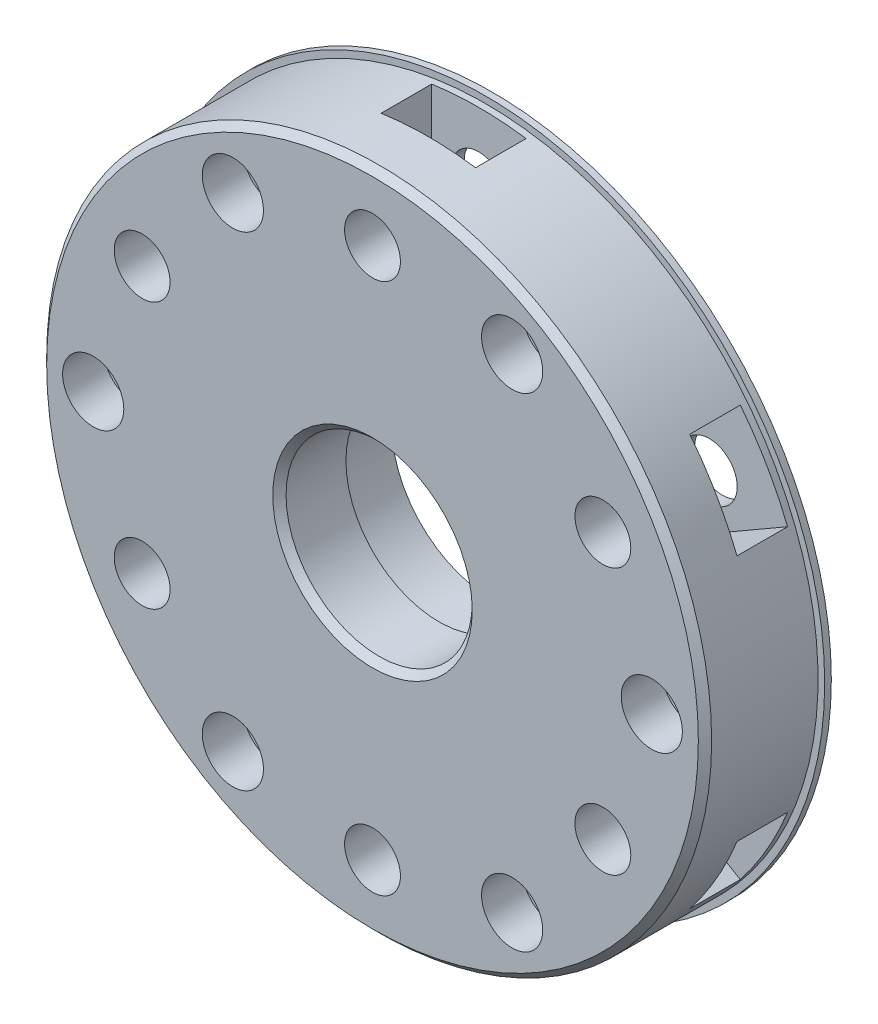
SolidWorks part; units mm, degrees
material "ABS"
ref_plane "Front Plane" through (0, 0, 0) normal (0, 0, 1) x (1, 0, 0)
ref_plane "Top Plane" through (0, 0, 0) normal (0, 1, 0) x (1, 0, 0)
ref_plane "Right Plane" through (0, 0, 0) normal (1, 0, 0) x (0, 0, -1)
sketch "Output Master Sketch" plane through (0, 0, 0) normal (0, 0, 1) x (1, 0, 0)
  circle A0 centre (0, 0) radius 21 construction
  circle A1 centre (21, 0) radius 3.05 construction
  circle A2 centre (10.5, -18.1865) radius 3.05 construction
  circle A3 centre (-10.5, -18.1865) radius 3.05 construction
  circle A4 centre (-21, 0) radius 3.05 construction
  circle A5 centre (-10.5, 18.1865) radius 3.05 construction
  circle A6 centre (10.5, 18.1865) radius 3.05 construction
  circle A7 centre (0, 0) radius 25
  point P17 (0, 0)
extrude "Boss-Extrude1" add sketch "Output Master Sketch" along normal blind 9
sketch "Sketch4" plane through (0, 0, 0) normal (0, 0, 1) x (1, 0, 0)
  circle A0 centre (21, 0) radius 3.05
  circle A1 centre (21, 0) radius 3.05 construction
  circle A2 centre (10.5, -18.1865) radius 3.05
  circle A3 centre (-10.5, -18.1865) radius 3.05
  circle A4 centre (-21, 0) radius 3.05
  circle A5 centre (-10.5, 18.1865) radius 3.05
  circle A6 centre (10.5, 18.1865) radius 3.05
  point P17 (0, 0)
  dimension "D1" = 6
extrude "Cut-Extrude1" cut sketch "Sketch4" along normal blind 4
sketch "Sketch5" plane through (0, 0, 0) normal (0, 0, -1) x (-1, 0, 0)
  circle A0 centre (0, 0) radius 25
  circle A1 centre (0, 0) radius 25.5
  circle A2 centre (0, 0) radius 25 construction
  dimension "D1" = 0.5
extrude "Boss-Extrude2" add sketch "Sketch5" against normal blind 0.5
sketch "Sketch6" plane through (0, 0, 0) normal (0, 0, -1) x (-1, 0, 0)
  circle A0 centre (-21, 0) radius 1.55
  circle A1 centre (-10.5, 18.1865) radius 1.55
  circle A2 centre (10.5, 18.1865) radius 1.55
  circle A3 centre (21, 0) radius 1.55
  circle A4 centre (10.5, -18.1865) radius 1.55
  circle A5 centre (-10.5, -18.1865) radius 1.55
  point P15 (0, 0)
  dimension "D1" = 3.1
  dimension "D2" = 6
extrude "Cut-Extrude2" cut sketch "Sketch6" against normal through all
sketch "Sketch7" plane through (0, 0, 9) normal (0, 0, 1) x (1, 0, 0)
  circle A0 centre (-21, 0) radius 2.3
  circle A1 centre (-10.5, 18.1865) radius 2.3
  circle A2 centre (10.5, 18.1865) radius 2.3
  circle A3 centre (21, 0) radius 2.3
  circle A4 centre (10.5, -18.1865) radius 2.3
  circle A5 centre (-10.5, -18.1865) radius 2.3
  point P16 (0, 0)
  dimension "D1" = 4.6
  dimension "D2" = 6
extrude "Cut-Extrude3" cut sketch "Sketch7" against normal blind 3.1
chamfer "Chamfer1" distance 0.5 angle 45 1 edges at (25, 0, 9)
sketch "Sketch8" plane through (0, 0, 0) normal (0, 0, -1) x (-1, 0, 0)
  circle A0 centre (0, 0) radius 7
  dimension "D1" = 14
extrude "Cut-Extrude4" cut sketch "Sketch8" against normal blind 10
sketch "Sketch9" plane through (0, 0, 0) normal (0, 0, -1) x (-1, 0, 0)
  circle A0 centre (0, 0) radius 7.55
  dimension "D1" = 15.1
extrude "Cut-Extrude5" cut sketch "Sketch9" against normal blind 4
sketch "Sketch10" plane through (0, 0, 9) normal (0, 0, 1) x (1, 0, 0)
  line L1 (0, 20) -> (-17.3205, 10) construction
  line L2 (-17.3205, 10) -> (-17.3205, -10) construction
  line L3 (-17.3205, -10) -> (0, -20) construction
  line L4 (0, -20) -> (17.3205, -10) construction
  line L5 (17.3205, -10) -> (17.3205, 10) construction
  line L6 (17.3205, 10) -> (0, 20) construction
  circle A0 centre (0, 0) radius 20 construction
  circle A1 centre (0, 20) radius 2.1
  circle A2 centre (17.3205, 10) radius 2.1
  circle A3 centre (17.3205, -10) radius 2.1
  circle A4 centre (0, -20) radius 2.1
  circle A5 centre (-17.3205, -10) radius 2.1
  circle A6 centre (-17.3205, 10) radius 2.1
  point P22 (0, 0)
  dimension "D1" = 40
  dimension "D2" = 4.2
  dimension "D3" = 6
extrude "M4 Thru" cut sketch "Sketch10" against normal through all
chamfer "Chamfer3" distance 0.5 angle 45 1 edges at (7, 0, 9)
sketch "Sketch11" plane through (0, 0, 9) normal (0, 0, 1) x (1, 0, 0)
  line L1 (0, 24.0992) -> (-3.55, 22.0496)
  line L2 (-3.55, 22.0496) -> (-3.55, 17.9504)
  line L3 (-3.55, 17.9504) -> (0, 15.9008)
  line L4 (0, 15.9008) -> (3.55, 17.9504)
  line L5 (3.55, 17.9504) -> (3.55, 22.0496)
  line L6 (3.55, 22.0496) -> (0, 24.0992)
  circle A0 centre (0, 20) radius 3.55 construction
  dimension "D1" = 7.1
extrude "M4 Hexnut Cut" cut sketch "Sketch11" along normal blind 3.8 from offset 8 offset against normal yes
ref_plane "Plane2" through (0, 22.0496, 0) normal (0, 1, 0) x (1, 0, 0)
sketch "Sketch12" plane through (0, 22.0496, 0) normal (0, 1, 0) x (1, 0, 0)
  line L1 (-3.55, -1) -> (3.55, -1)
  line L2 (-3.55, -1) -> (-3.55, -4.8)
  line L3 (-3.55, -4.8) -> (3.55, -4.8)
  line L4 (3.55, -1) -> (3.55, -4.8)
extrude "M4 Hexnut Slot" cut sketch "Sketch12" along normal through all contours L2 L1 L4 L3
pattern_circular "M4 Hexnut Pattern" count 6 over 360 about axis through (0, 0, 0) along (0, 0, 1) of "M4 Hexnut Cut", "M4 Hexnut Slot"
